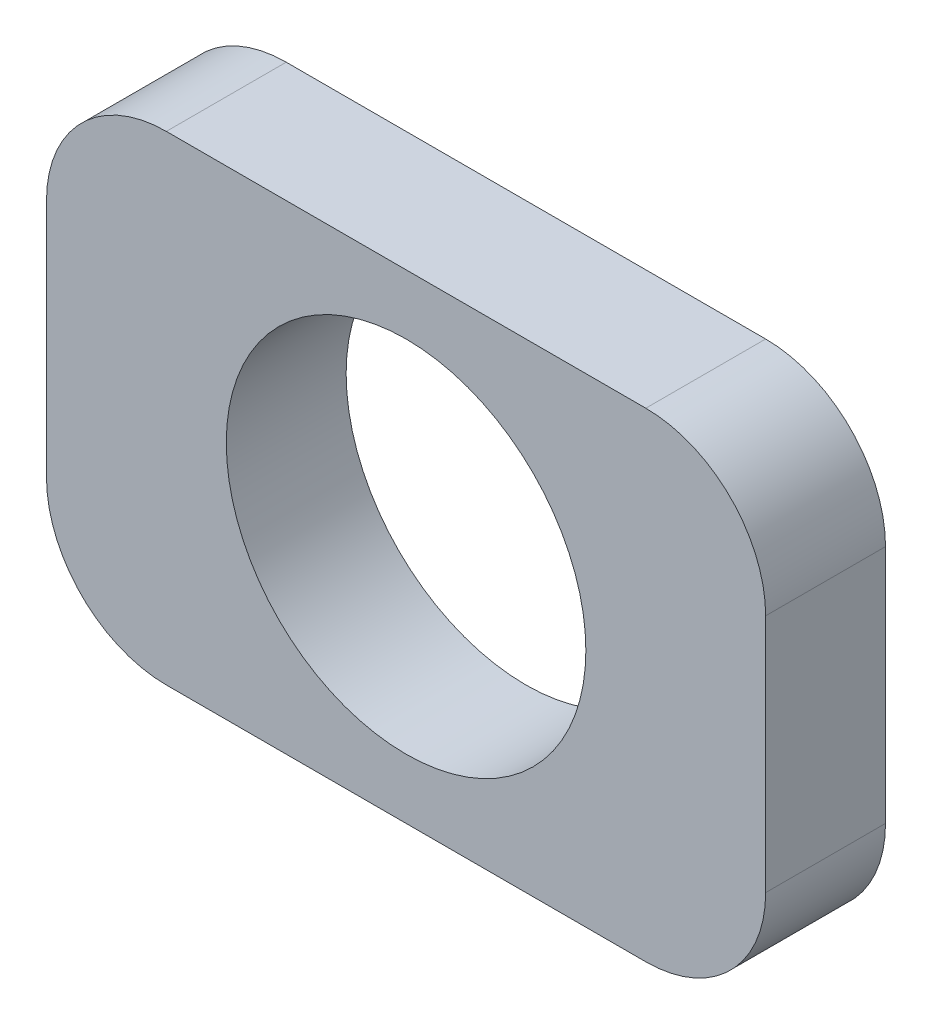
SolidWorks part; units mm, degrees
ref_plane "Спереди" through (0, 0, 0) normal (0, 0, 1) x (1, 0, 0)
ref_plane "Сверху" through (0, 0, 0) normal (0, 1, 0) x (1, 0, 0)
ref_plane "Справа" through (0, 0, 0) normal (1, 0, 0) x (0, 0, -1)
other "Configuration Table"
sketch "Эскиз1" plane through (0, 0, 0) normal (0, 0, 1) x (1, 0, 0)
  line L0 (0, 20) -> (60, 20) construction
  line L1 (10, 0) -> (50, 0)
  line L2 (0, 10) -> (0, 30)
  line L3 (10, 40) -> (50, 40)
  line L4 (60, 10) -> (60, 30)
  line L5 (30, 40) -> (30, 0) construction
  circle A0 centre (30, 20) radius 15
  arc A1 (10, 0) -> (0, 10) centre (10, 10) cw
  arc A2 (50, 0) -> (60, 10) centre (50, 10) ccw
  arc A3 (50, 40) -> (60, 30) centre (50, 30) cw
  arc A4 (0, 30) -> (10, 40) centre (10, 30) cw
  point P13 (0, 0)
  dimension "D3" = 40
  dimension "D1" = 10
  dimension "D4" = 30
  dimension "D2" = 60
extrude "Бобышка-Вытянуть1" add sketch "Эскиз1" along normal blind 10
sketch "Эскиз2" plane through (0, 0, 0) normal (0, 1, 0) x (1, 0, 0)
